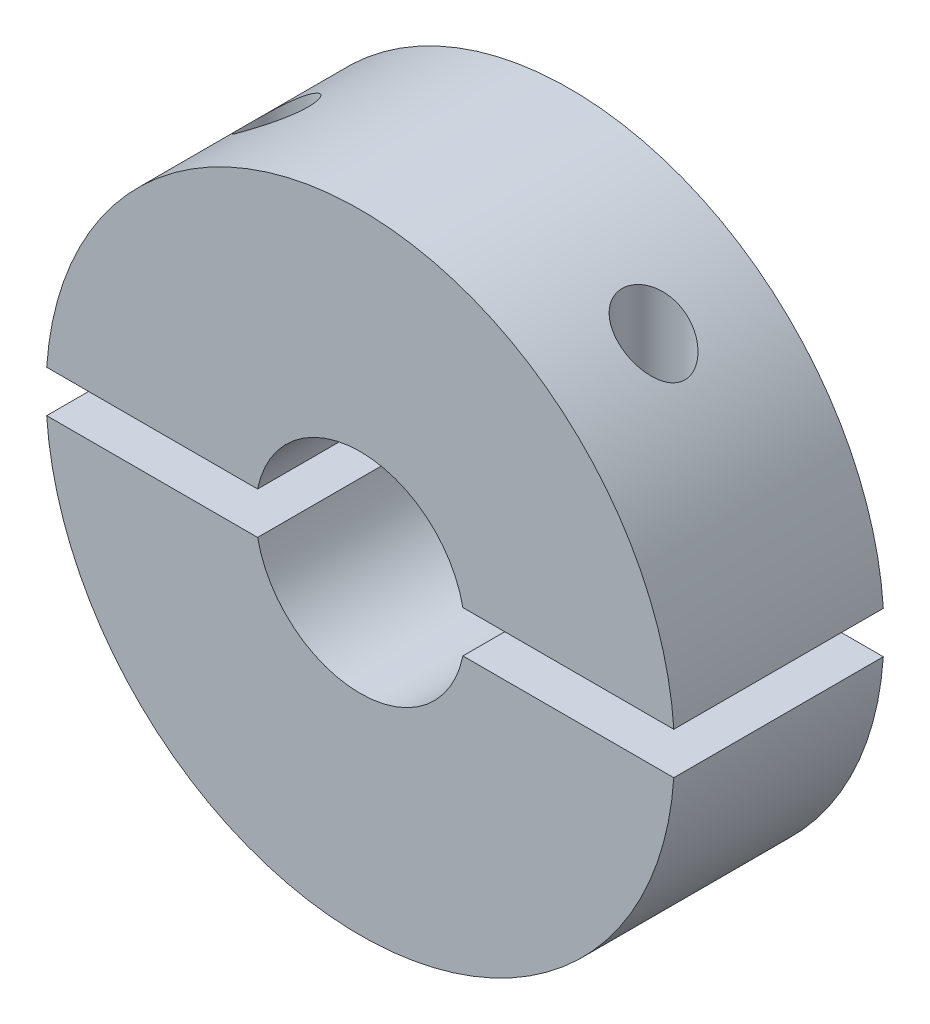
SolidWorks part; units mm, degrees
material "6063-T5"
ref_plane "前视基准面" through (0, 0, 0) normal (0, 0, 1) x (1, 0, 0)
ref_plane "上视基准面" through (0, 0, 0) normal (0, 1, 0) x (1, 0, 0)
ref_plane "右视基准面" through (0, 0, 0) normal (1, 0, 0) x (0, 0, -1)
sketch "草图1" plane through (0, 0, 0) normal (0, 0, 1) x (1, 0, 0)
  circle A0 centre (0, 0) radius 5
  circle A1 centre (0, 0) radius 15
  dimension "D1" = 10
  dimension "D2" = 30
extrude "凸台-拉伸1" add sketch "草图1" along normal mid plane 10
sketch "草图2" plane through (0, 0, 5) normal (0, 0, 1) x (1, 0, 0)
  line L1 (-22.7859, -1) -> (22.7859, -1)
  line L2 (-22.7859, -1) -> (-22.7859, 1)
  line L3 (-22.7859, 1) -> (22.7859, 1)
  line L4 (22.7859, -1) -> (22.7859, 1)
  line L5 (0, 1) -> (0, -1) construction
  line L6 (-22.7859, 0) -> (22.7859, 0) construction
  point P0 (0, 0)
  dimension "D1" = 2
  dimension "D2" = 45.5718
extrude "切除-拉伸1" cut sketch "草图2" against normal blind 33
sketch "草图4" plane through (0, 0, 0) normal (0, 1, 0) x (1, 0, 0)
  line L0 (-9, 0) -> (9, 0) construction
  circle A0 centre (9, 0) radius 1.5
  circle A1 centre (-9, 0) radius 1.5
  point P4 (0, 0)
  dimension "D2" = 3
  dimension "D1" = 18
extrude "切除-拉伸2" cut sketch "草图4" against normal mid plane 83
